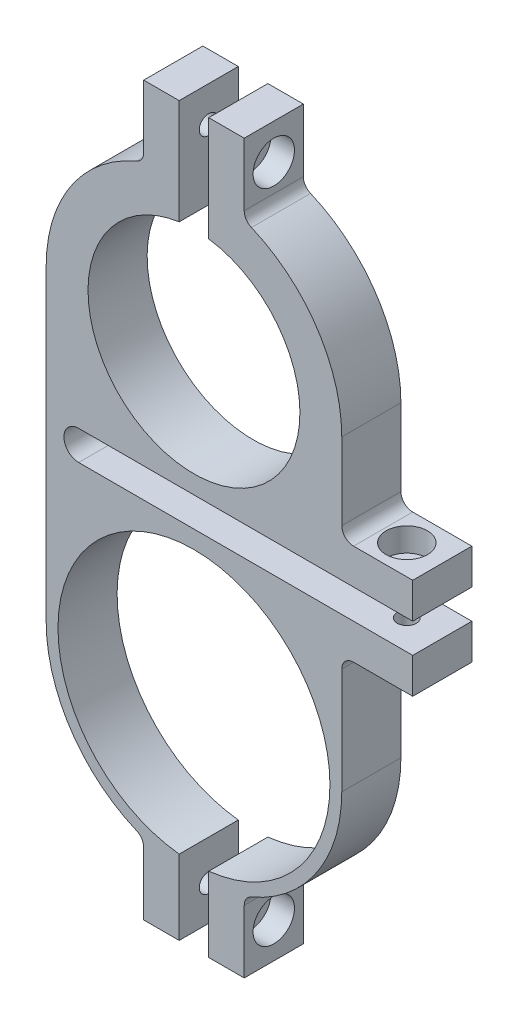
SolidWorks part; units mm, degrees
ref_plane "Front Plane" through (0, 0, 0) normal (0, 0, 1) x (1, 0, 0)
ref_plane "Top Plane" through (0, 0, 0) normal (0, 1, 0) x (1, 0, 0)
ref_plane "Right Plane" through (0, 0, 0) normal (1, 0, 0) x (0, 0, -1)
sketch "Sketch1" plane through (0, 0, 0) normal (0, 0, 1) x (1, 0, 0)
  line L0 (-39.6875, 82.55) -> (-39.6875, 0)
  line L1 (58.7375, 49.2125) -> (-30.9563, 49.2125)
  line L2 (-30.9563, 41.275) -> (58.7375, 41.275)
  line L3 (3.9688, -36.2962) -> (3.9688, -56.3731)
  line L4 (0, 82.55) -> (0, 0) construction
  line L5 (-13.4937, -37.3231) -> (-13.4937, -56.3731)
  line L6 (3.9688, -56.3731) -> (13.4938, -56.3731)
  line L7 (-3.9687, -56.3731) -> (-13.4937, -56.3731)
  line L8 (13.4938, -37.3231) -> (13.4938, -56.3731)
  line L9 (-3.9687, -36.2962) -> (-3.9687, -56.3731)
  line L11 (13.4938, 119.8731) -> (13.4937, 138.9231)
  line L12 (-3.9688, 138.9231) -> (-13.4938, 138.9231)
  line L13 (3.9687, 138.9231) -> (13.4937, 138.9231)
  line L14 (3.9687, 138.9231) -> (3.9688, 110.7198)
  line L15 (-13.4938, 119.8731) -> (-13.4938, 138.9231)
  line L16 (58.7375, 58.7375) -> (58.7375, 49.2125)
  line L17 (39.6875, 58.7375) -> (58.7375, 58.7375)
  line L18 (-3.9688, 138.9231) -> (-3.9688, 110.7198)
  line L19 (39.6875, 0) -> (39.6875, 31.75)
  line L20 (39.6875, 31.75) -> (58.7375, 31.75)
  line L21 (58.7375, 31.75) -> (58.7375, 41.275)
  line L22 (39.6875, 82.55) -> (39.6875, 58.7375)
  line L23 (3.9687, 138.9231) -> (-3.9688, 138.9231) construction
  line L24 (58.7375, 41.275) -> (58.7375, 49.2125) construction
  line L25 (3.9688, -56.3731) -> (-3.9687, -56.3731) construction
  arc A0 (3.9688, -36.2962) -> (-3.9687, -36.2962) centre (0, 0) ccw
  arc A1 (-3.9688, 110.7198) -> (3.9688, 110.7198) centre (0, 82.55) ccw
  arc A2 (13.4938, 119.8731) -> (39.6875, 82.55) centre (0, 82.55) cw
  arc A3 (-39.6875, 0) -> (-13.4937, -37.3231) centre (0, 0) ccw
  arc A4 (-30.9563, 49.2125) -> (-30.9563, 41.275) centre (-30.9563, 45.2437) ccw
  arc A5 (13.4938, -37.3231) -> (39.6875, 0) centre (0, 0) ccw
  arc A6 (-39.6875, 82.55) -> (-13.4938, 119.8731) centre (0, 82.55) cw
  circle A7 centre (-30.9563, 45.2437) radius 3.9688 construction
  circle A8 centre (0, 0) radius 36.5125 construction
  circle A9 centre (0, 82.55) radius 28.448 construction
  circle A10 centre (0, 0) radius 39.6875 construction
  point P5 (-34.925, 45.2437)
  point P14 (0, 36.5125)
  dimension "D2" = 7.9375
  dimension "D4" = 56.896
  dimension "D5" = 73.025
  dimension "D7" = 79.375
  dimension "D1" = 4.7625
  dimension "D3" = 82.55
  dimension "D6" = 9.525
  dimension "D8" = 19.05
  dimension "D9" = 4.7625
extrude "Extrude1" add sketch "Sketch1" along normal mid plane 15.875
hole_wizard "CBORE for 1/4 Socket Head Cap Screw1" positions "Sketch3" profile "Sketch2" counterbore size "1/4" standard "Ansi Inch"
sketch "Sketch3" plane through (13.4938, 0, 0) normal (1, 0, 0) x (0, 0, -1)
  line L0 (7.9375, 138.9231) -> (-7.9375, 119.8731) construction
  point P0 (0, 129.3981)
sketch "Sketch2" plane through (13.4938, 129.3981, 0) normal (0, 1, 0) x (0, 0, -1)
  line L0 (0, 0) -> (0, 9.525)
  line L1 (0, 9.525) -> (3.3782, 9.525)
  line L3 (3.3782, 9.525) -> (3.3782, 6.35)
  line L4 (3.3782, 6.35) -> (5.5562, 6.35)
  line L5 (5.5562, 6.35) -> (5.5562, 0)
  line L7 (5.5562, 0) -> (0, 0)
  line L11 (0, -6.35) -> (0, 107.95) construction
  dimension "Thru Hole Dia." = 6.7564
  dimension "Thru Hole Depth" = 9.525
  dimension "C'Bore Dia." = 11.1125
  dimension "C'Bore Depth" = 6.35
hole_wizard "1/4-20 Tapped Hole1" positions "Sketch5" profile "Sketch4" tap size "1/4-20" standard "Ansi Inch" end condition through all
sketch "Sketch5" plane through (-3.9688, 0, 0) normal (1, 0, 0) x (0, 0, -1)
  point P0 (0, 129.3981)
sketch "Sketch4" plane through (-3.9688, 129.3981, 0) normal (0, 1, 0) x (0, 0, -1)
  line L0 (0, 0) -> (0, 35.7188)
  line L1 (0, 35.7188) -> (2.5527, 35.7188)
  line L2 (2.5527, 35.7188) -> (2.5527, 0)
  line L5 (2.5527, 0) -> (0, 0)
  line L11 (0, -6.35) -> (0, 107.95) construction
  dimension "Thru Tap Drill Dia." = 5.1054
  dimension "Thru Tap Drill Depth" = 35.7188
cosmetic thread "Hole Thread1" parameters "D2"=6.35
hole_wizard "CBORE for 1/4 Socket Head Cap Screw2" positions "Sketch10" profile "Sketch11" counterbore size "1/4" standard "Ansi Inch"
sketch "Sketch10" plane through (0, 58.7375, 0) normal (0, 1, 0) x (0, 0, -1)
  line L0 (7.9375, -39.6875) -> (-7.9375, -58.7375) construction
  point P0 (0, -49.2125)
sketch "Sketch11" plane through (49.2125, 58.7375, 0) normal (1, 0, 0) x (0, 0, 1)
  line L0 (0, 0) -> (0, 9.525)
  line L1 (0, 9.525) -> (3.3782, 9.525)
  line L3 (3.3782, 9.525) -> (3.3782, 6.35)
  line L4 (3.3782, 6.35) -> (5.5562, 6.35)
  line L5 (5.5562, 6.35) -> (5.5562, 0)
  line L7 (5.5562, 0) -> (0, 0)
  line L11 (0, -6.35) -> (0, 107.95) construction
  dimension "Thru Hole Dia." = 6.7564
  dimension "Thru Hole Depth" = 9.525
  dimension "C'Bore Dia." = 11.1125
  dimension "C'Bore Depth" = 6.35
hole_wizard "1/4-20 Tapped Hole3" positions "Sketch13" profile "Sketch15" tap size "1/4-20" standard "Ansi Inch" end condition through all
sketch "Sketch13" plane through (0, 41.275, 0) normal (0, 1, 0) x (-1, 0, 0)
  point P0 (-49.2125, 0)
sketch "Sketch15" plane through (49.2125, 41.275, 0) normal (1, 0, 0) x (0, 0, 1)
  line L0 (0, 0) -> (0, 97.6481)
  line L1 (0, 97.6481) -> (2.5527, 97.6481)
  line L2 (2.5527, 97.6481) -> (2.5527, 0)
  line L5 (2.5527, 0) -> (0, 0)
  line L11 (0, -6.35) -> (0, 107.95) construction
  dimension "Thru Tap Drill Dia." = 5.1054
  dimension "Thru Tap Drill Depth" = 97.6481
cosmetic thread "Hole Thread3" parameters "D2"=6.35
hole_wizard "CBORE for 1/4 Socket Head Cap Screw3" positions "Sketch16" profile "Sketch17" counterbore size "1/4" standard "Ansi Inch"
sketch "Sketch16" plane through (13.4938, 0, 0) normal (1, 0, 0) x (0, 0, -1)
  line L0 (7.9375, -37.3231) -> (-7.9375, -56.3731) construction
  point P0 (0, -46.8481)
sketch "Sketch17" plane through (13.4938, -46.8481, 0) normal (0, 1, 0) x (0, 0, -1)
  line L0 (0, 0) -> (0, 9.525)
  line L1 (0, 9.525) -> (3.3782, 9.525)
  line L3 (3.3782, 9.525) -> (3.3782, 6.35)
  line L4 (3.3782, 6.35) -> (5.5562, 6.35)
  line L5 (5.5562, 6.35) -> (5.5562, 0)
  line L7 (5.5562, 0) -> (0, 0)
  line L11 (0, -6.35) -> (0, 107.95) construction
  dimension "Thru Hole Dia." = 6.7564
  dimension "Thru Hole Depth" = 9.525
  dimension "C'Bore Dia." = 11.1125
  dimension "C'Bore Depth" = 6.35
hole_wizard "1/4-20 Tapped Hole4" positions "Sketch19" profile "Sketch21" tap size "1/4-20" standard "Ansi Inch" end condition through all
sketch "Sketch19" plane through (-3.9688, 0, 0) normal (1, 0, 0) x (0, 0, -1)
  point P0 (0, -46.8481)
sketch "Sketch21" plane through (-3.9687, -46.8481, 0) normal (0, 1, 0) x (0, 0, -1)
  line L0 (0, 0) -> (0, 35.7188)
  line L1 (0, 35.7188) -> (2.5527, 35.7188)
  line L2 (2.5527, 35.7188) -> (2.5527, 0)
  line L5 (2.5527, 0) -> (0, 0)
  line L11 (0, -6.35) -> (0, 107.95) construction
  dimension "Thru Tap Drill Dia." = 5.1054
  dimension "Thru Tap Drill Depth" = 35.7188
cosmetic thread "Hole Thread4" parameters "D2"=6.35
fillet "Fillet1" radius 3.175 6 edges at (39.6875, 58.7375, 0) (13.4938, 119.8731, 0) (-13.4938, 119.8731, 0) (-13.4937, -37.3231, 0) (13.4938, -37.3231, 0) (39.6875, 31.75, 0)
